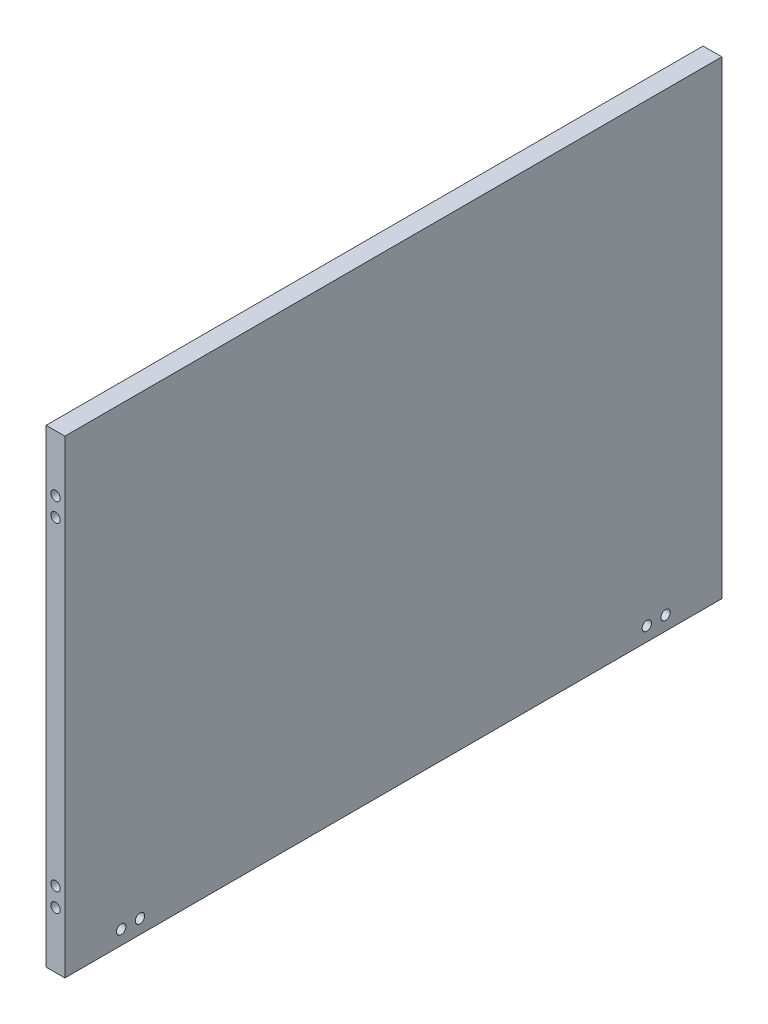
SolidWorks part; units mm, degrees
ref_plane "Front Plane" through (0, 0, 0) normal (0, 0, 1) x (1, 0, 0)
ref_plane "Top Plane" through (0, 0, 0) normal (0, 1, 0) x (1, 0, 0)
ref_plane "Right Plane" through (0, 0, 0) normal (1, 0, 0) x (0, 0, -1)
sketch "Sketch1" plane through (0, 0, 0) normal (1, 0, 0) x (0, 0, -1)
  line L1 (-175, 125) -> (175, 125)
  line L2 (-175, 125) -> (-175, -125)
  line L3 (-175, -125) -> (175, -125)
  line L4 (175, 125) -> (175, -125)
  line L5 (-175, 125) -> (175, -125) construction
  line L6 (-175, -125) -> (175, 125) construction
  point P0 (0, 0)
  dimension "D1" = 350
  dimension "D2" = 250
extrude "Boss-Extrude1" add sketch "Sketch1" along normal blind 10
sketch "Sketch2" plane through (0, 0, 175) normal (0, 0, 1) x (1, 0, 0)
  line L0 (10, 125) -> (0, 125) construction
  line L1 (10, -125) -> (0, -125) construction
  line L2 (0, 125) -> (0, -125) construction
  circle A0 centre (5, 95) radius 2.5
  circle A1 centre (5, 85) radius 2.5
  circle A2 centre (5, -85) radius 2.5
  circle A3 centre (5, -95) radius 2.5
  dimension "D6" = 5
  dimension "D1" = 30
  dimension "D2" = 30
  dimension "D3" = 10
  dimension "D4" = 10
  dimension "D5" = 5
extrude "Cut-Extrude1" cut sketch "Sketch2" against normal blind 10
mirror "Mirror1" about plane through (0, 0, 0) normal (0, 0, 1) of "Cut-Extrude1"
sketch "Sketch3" plane through (10, 0, 0) normal (1, 0, 0) x (0, 0, -1)
  line L2 (-175, 125) -> (-175, -125) construction
  line L3 (175, -125) -> (175, 125) construction
  line L4 (-175, -125) -> (175, -125) construction
  circle A0 centre (-145, -117.5) radius 2.5
  circle A1 centre (-135, -117.5) radius 2.5
  circle A2 centre (135, -117.5) radius 2.5
  circle A3 centre (145, -117.5) radius 2.5
  dimension "D6" = 5
  dimension "D1" = 10
  dimension "D2" = 10
  dimension "D3" = 30
  dimension "D4" = 30
  dimension "D5" = 7.5
extrude "Cut-Extrude2" cut sketch "Sketch3" against normal through all
